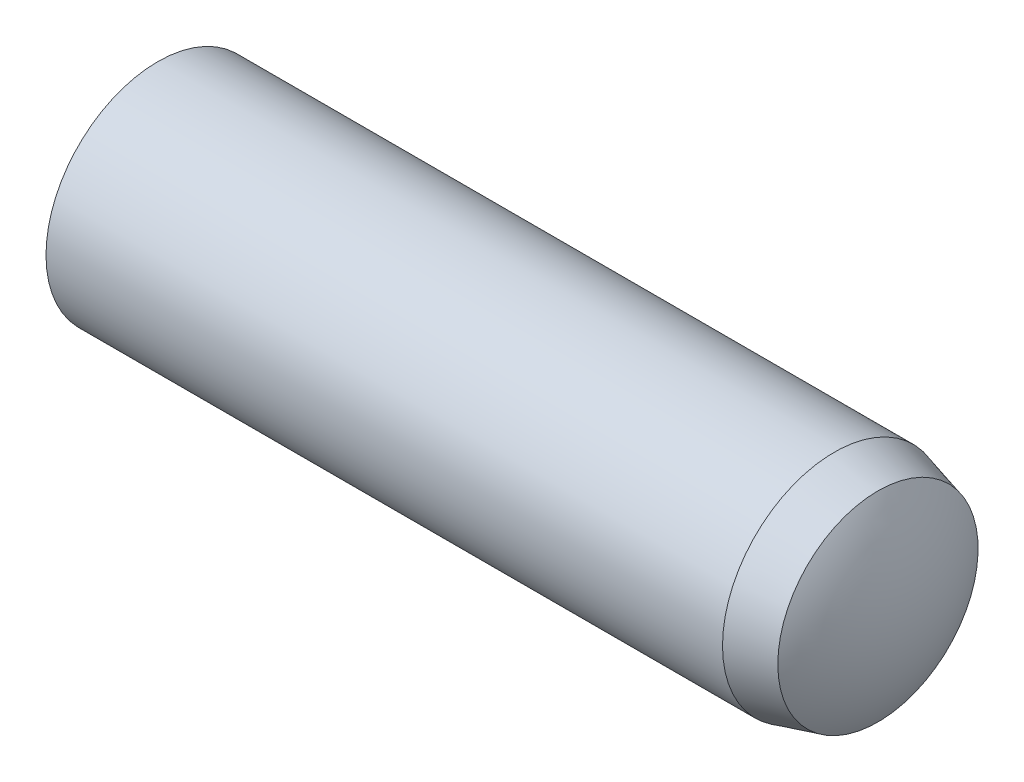
SolidWorks part; units mm, degrees
ref_plane "Front Plane" through (0, 0, 0) normal (0, 0, 1) x (1, 0, 0)
ref_plane "Top Plane" through (0, 0, 0) normal (0, 1, 0) x (1, 0, 0)
ref_plane "Right Plane" through (0, 0, 0) normal (1, 0, 0) x (0, 0, -1)
sketch "Sketch1" plane through (0, 0, 0) normal (0, 0, 1) x (1, 0, 0)
  line L0 (-3.5, 0) -> (3.5, 0) construction
  line L1 (3.5, 1) -> (3.5, -1) construction
  line L2 (-3.5, 1) -> (-3.5, -1) construction
  line L3 (2.85, 1) -> (2.85, -1) construction
  line L4 (-3.2, 1) -> (-3.2, -1) construction
  line L5 (-3.5, 0) -> (-3.2, 0) construction
  line L6 (3.5, 0) -> (2.85, 0) construction
  line L7 (3.24, 1) -> (3.24, -1) construction
  dimension "Dia" = 2
  dimension "Length" = 7
  dimension "D1" = 0.65
  dimension "D2" = 0.3
  dimension "D3" = 0.39
sketch "Sketch2" plane through (0, 0, 0) normal (1, 0, 0) x (0, 0, -1)
  circle A0 centre (0, 0) radius 1
extrude "Extrude1" add sketch "Sketch2" against normal up to vertex (3.5 mm away) and the other way up to vertex (3.5 mm away) up to point (-3.5, 0, 0) other way up to point (3.5, 0, 0)
sketch "Sketch5" plane through (0, 0, 0) normal (0, 0, 1) x (1, 0, 0)
  line L0 (2.85, 1) -> (2.85, 1.5)
  line L1 (2.85, 1.5) -> (4, 1.5)
  line L2 (4, 1.5) -> (4, 0)
  line L3 (3.5, 0) -> (4, 0)
  line L5 (-3.2, 1) -> (-3.2, 1.5)
  line L6 (-3.2, 1.5) -> (-4, 1.5)
  line L7 (-4, 1.5) -> (-4, 0)
  line L8 (2.85, 1) -> (3.24, 0.8955)
  line L10 (-3.5, 0) -> (-4, 0)
  line L11 (-3.5, 1) -> (-3.5, -1) construction
  line L13 (2.85, 1) -> (2.85, -1) construction
  line L15 (-3.5, 0) -> (3.5, 0) construction
  line L16 (3.24, 1) -> (3.24, -1) construction
  line L17 (3.5, 1) -> (3.5, -1) construction
  arc A0 (3.24, 0.8955) -> (3.5, 0) centre (1.8278, 0) cw
  arc A1 (-3.2, 1) -> (-3.5, 0) centre (-1.6833, 0) ccw
  dimension "D1" = 15
  dimension "D2" = 0.5
revolve "Cut-Revolve1" cut sketch "Sketch5" angle 360 about L0
equation "\"D1@Sketch1\" = \"Dia@Sketch1\"*.325"
equation "\"D2@Sketch1\" = \"Dia@Sketch1\"*.15"
equation "\"D3@Sketch1\" = \"D1@Sketch1\"*.6"
